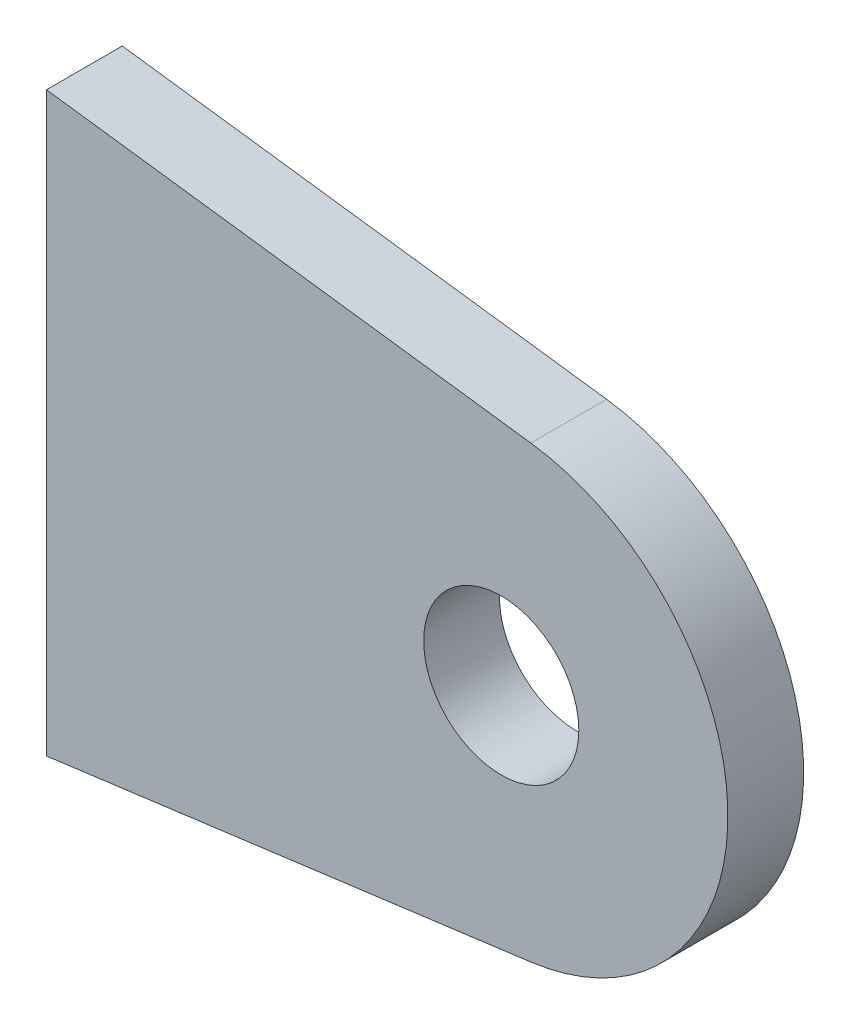
SolidWorks part; units mm, degrees
material "AISI 4130 Steel, annealed at 865C"
ref_plane "X-Y Datum" through (0, 0, 0) normal (0, 0, 1) x (1, 0, 0)
ref_plane "X-Z Datum" through (0, 0, 0) normal (0, 1, 0) x (1, 0, 0)
ref_plane "Y-Z Datum" through (0, 0, 0) normal (1, 0, 0) x (0, 0, -1)
sketch "Sketch1" plane through (-1053.7408, 0, 0) normal (0, 0, 1) x (1, 0, 0)
  line L0 (1054.9803, -9.4147) -> (1034.6908, -12.0859)
  line L1 (1054.9803, 9.4147) -> (1034.6908, 12.0859)
  line L2 (1034.6908, -12.0859) -> (1034.6908, 12.0859)
  circle A0 centre (1053.7408, 0) radius 3.25
  circle A1 centre (1053.7408, 0) radius 9.4959
  circle A4 centre (1053.7408, 0) radius 11.43 construction
  dimension "D3" = 18.9919
  dimension "D4" = 6.5
  dimension "D5" = 22.86
  dimension "D1" = 15
  dimension "D2" = 19.05
extrude "Boss-Extrude1" add sketch "Sketch1" along normal blind 3.175
